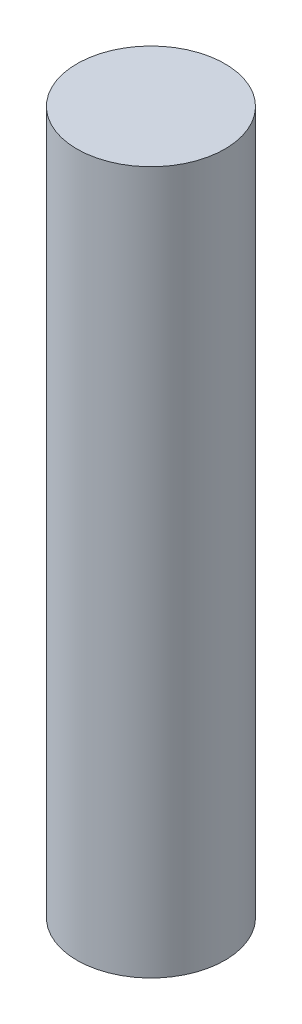
SolidWorks part; units mm, degrees
ref_plane "Front Plane" through (0, 0, 0) normal (0, 0, 1) x (1, 0, 0)
ref_plane "Top Plane" through (0, 0, 0) normal (0, 1, 0) x (1, 0, 0)
ref_plane "Right Plane" through (0, 0, 0) normal (1, 0, 0) x (0, 0, -1)
sketch "Sketch1" plane through (0, 0, 0) normal (0, 1, 0) x (1, 0, 0)
  circle A0 centre (0, 0) radius 4
  dimension "D1" = 8
extrude "Boss-Extrude1" add sketch "Sketch1" along normal mid plane 38
